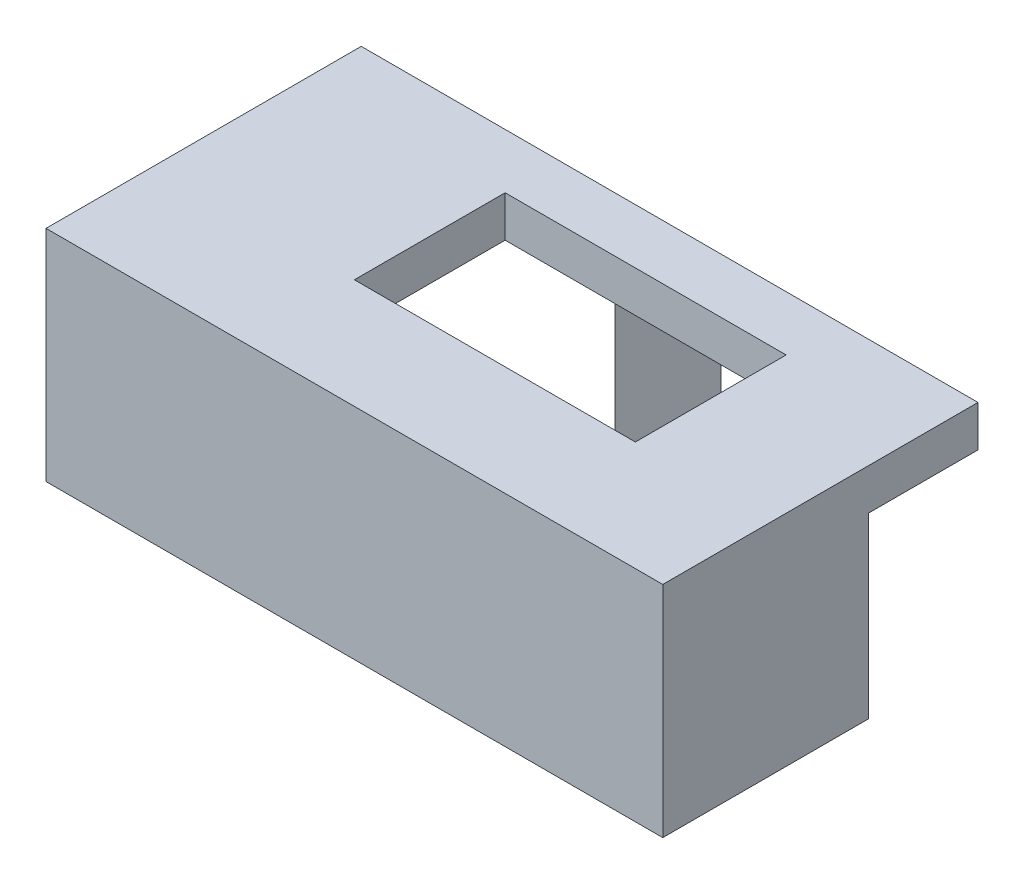
SolidWorks part; units mm, degrees
ref_plane "Front Plane" through (0, 0, 0) normal (0, 0, 1) x (1, 0, 0)
ref_plane "Top Plane" through (0, 0, 0) normal (0, 1, 0) x (1, 0, 0)
ref_plane "Right Plane" through (0, 0, 0) normal (1, 0, 0) x (0, 0, -1)
sketch "Sketch1" plane through (0, 0, 0) normal (0, 1, 0) x (1, 0, 0)
  line L1 (0, 0) -> (90, 0)
  line L2 (0, 0) -> (0, 46)
  line L3 (0, 46) -> (90, 46)
  line L4 (90, 0) -> (90, 46)
  line L5 (29, 16) -> (70, 16)
  line L6 (29, 16) -> (29, 38)
  line L7 (29, 38) -> (70, 38)
  line L8 (70, 16) -> (70, 38)
  dimension "D1" = 90
  dimension "D2" = 8
  dimension "D3" = 22
  dimension "D4" = 41
  dimension "D5" = 20
  dimension "D6" = 46
extrude "Boss-Extrude1" add sketch "Sketch1" along normal blind 6
sketch "Sketch2" plane through (0, 0, 0) normal (0, -1, 0) x (1, 0, 0)
  line L1 (0, 0) -> (4, 0)
  line L2 (0, 0) -> (0, -30)
  line L3 (0, -30) -> (4, -30)
  line L4 (4, -2) -> (4, -30)
  line L5 (37.5, -46) -> (52.5, -46)
  line L6 (90, 0) -> (82, 0)
  line L7 (90, 0) -> (90, -30)
  line L8 (90, -30) -> (86, -30)
  line L9 (86, -2) -> (86, -30)
  line L10 (90, -46) -> (0, -46) construction
  line L11 (52.5, -46) -> (45, -38)
  line L12 (70, -38) -> (29, -38) construction
  line L13 (45, -38) -> (37.5, -46)
  line L14 (90, 0) -> (90, -46) construction
  line L15 (4, 0) -> (82, 0)
  line L16 (4, -2) -> (86, -2)
  point P21 (81.3529, -2)
  dimension "D1" = 4
  dimension "D2" = 8
  dimension "D3" = 30
  dimension "D4" = 15
  dimension "D5" = 45
  dimension "D6" = 2
  dimension "D7" = 4
  dimension "D8" = 4
extrude "Boss-Extrude2" add sketch "Sketch2" along normal blind 26
